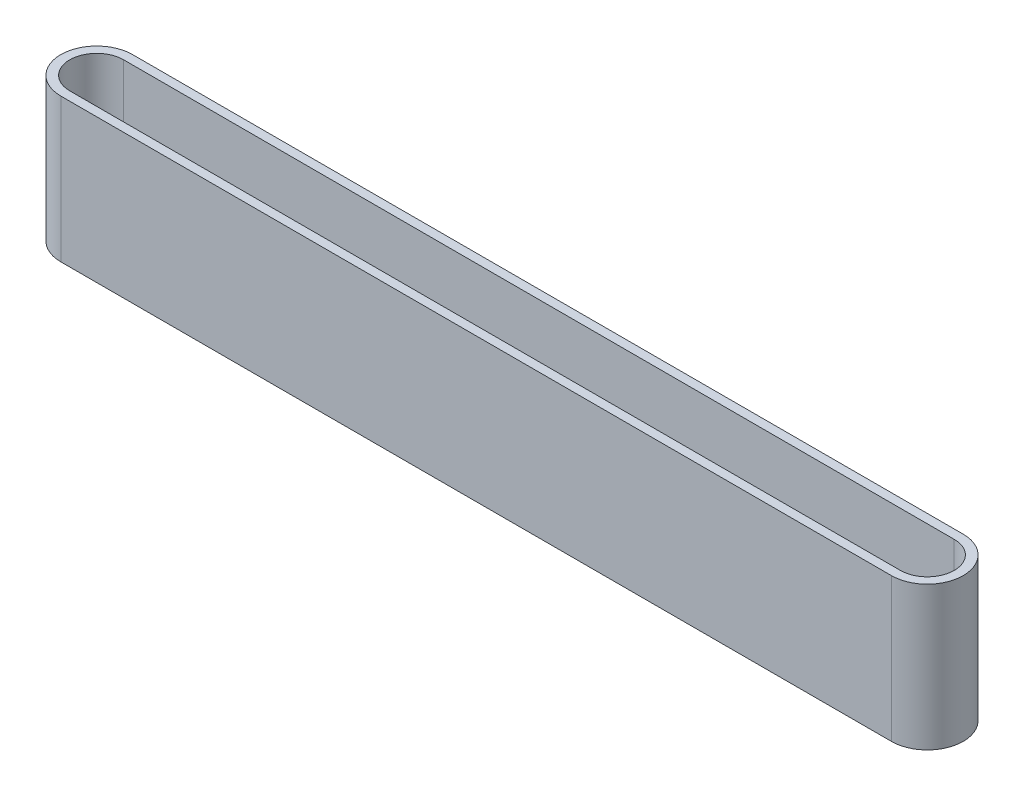
SolidWorks part; units mm, degrees
ref_plane "Front Plane" through (0, 0, 0) normal (0, 0, 1) x (1, 0, 0)
ref_plane "Top Plane" through (0, 0, 0) normal (0, 1, 0) x (1, 0, 0)
ref_plane "Right Plane" through (0, 0, 0) normal (1, 0, 0) x (0, 0, -1)
sketch "Sketch1" plane through (0, 0, 0) normal (0, 1, 0) x (1, 0, 0)
  line L0 (0, 0) -> (47571.1794, 0) construction
  line L1 (-39.5477, 3) -> (53.0023, 3)
  line L2 (-39.5477, -3) -> (53.0023, -3)
  circle A0 centre (-39.5477, 0) radius 3 construction
  circle A1 centre (53.0023, 0) radius 3 construction
  arc A2 (-39.5477, 3) -> (-39.5477, -3) centre (-39.5477, 0) ccw
  arc A3 (53.0023, 3) -> (53.0023, -3) centre (53.0023, 0) cw
  dimension "D2" = 6
  dimension "D1" = 92.55
extrude "Extrude-Thin1" add sketch "Sketch1" along normal blind 16 thin thin type one direction wall 1
